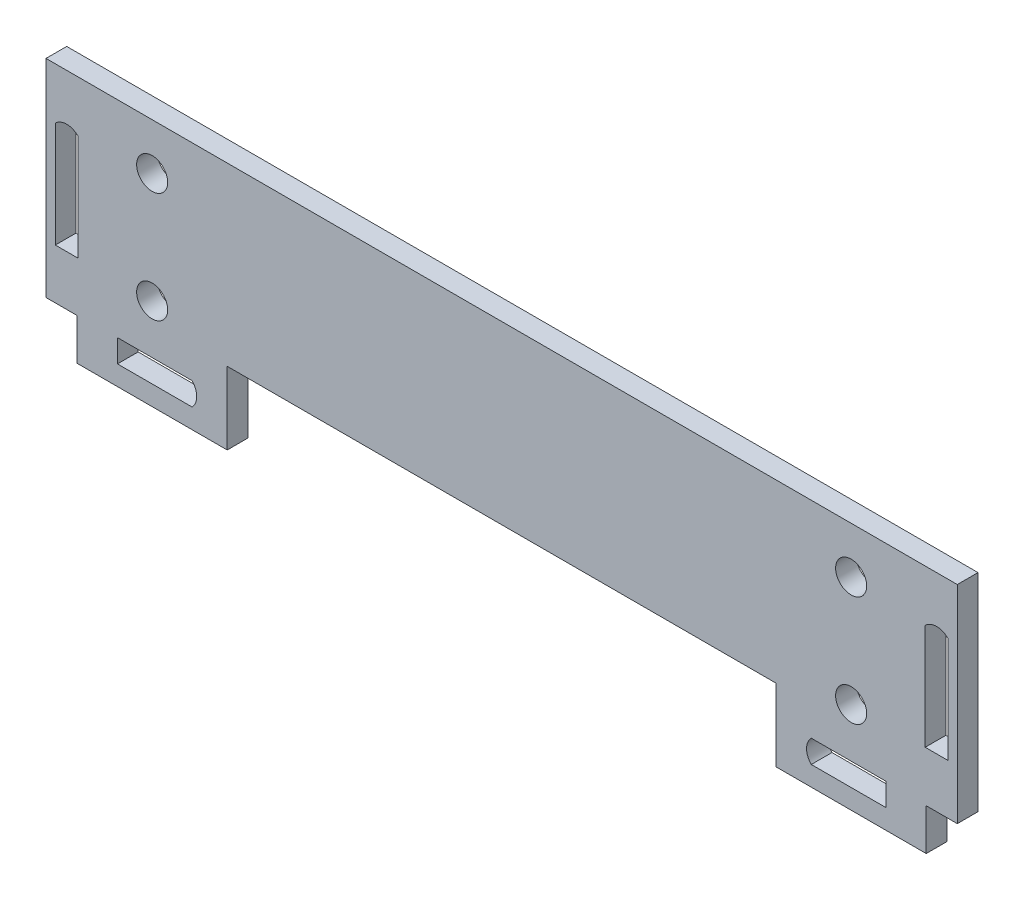
SolidWorks part; units mm, degrees
ref_plane "前视基准面" through (0, 0, 0) normal (0, 0, 1) x (1, 0, 0)
ref_plane "上视基准面" through (0, 0, 0) normal (0, 1, 0) x (1, 0, 0)
ref_plane "右视基准面" through (0, 0, 0) normal (1, 0, 0) x (0, 0, -1)
sketch "草图3" plane through (0, 0, 0) normal (0, 0, 1) x (1, 0, 0)
  line L2 (41, 20.0098) -> (-41, 20.0098)
  line L4 (43.1, 4.8498) -> (40.9, 15.0498) construction
  line L5 (-37, 0.0098) -> (-37, -1.9902) construction
  line L6 (-30, -1.9902) -> (-37, -1.9902) construction
  line L7 (-30, 0.0098) -> (-30, -1.9902) construction
  line L8 (-30, 0.0098) -> (-37, 0.0098) construction
  line L9 (-41, -1.9902) -> (-41, 0.0098) construction
  line L10 (0, -1.9902) -> (0, 3.216) construction
  line L11 (30, 0.0098) -> (37, 0.0098) construction
  line L12 (30, 0.0098) -> (30, -1.9902) construction
  line L13 (30, -1.9902) -> (37, -1.9902) construction
  line L14 (37, 0.0098) -> (37, -1.9902) construction
  line L24 (37.1, -2.0902) -> (29.9, -2.0902)
  line L25 (37.1, -2.0902) -> (37.1, 0.1098)
  line L26 (37.1, 0.1098) -> (29.9, 0.1098)
  line L30 (41, 0.0098) -> (41, -3.9902)
  line L81 (-44, 0.0098) -> (-44, 5.0098)
  line L82 (-41, 0.0098) -> (-44, 0.0098)
  line L87 (-44, 15.0098) -> (-44, 20.0098)
  line L88 (-44, 20.0098) -> (-41, 20.0098)
  line L89 (-41, 0.0098) -> (-41, -3.9902)
  line L90 (-37.1, 0.1098) -> (-29.9, 0.1098)
  line L91 (-37.1, -2.0902) -> (-37.1, 0.1098)
  line L92 (-37.1, -2.0902) -> (-29.9, -2.0902)
  line L93 (41, -3.9902) -> (26.5, -3.9902)
  line L94 (26.5, -3.9902) -> (26.5, 3.0098)
  line L95 (-41, -3.9902) -> (-26.5, -3.9902)
  line L96 (-26.5, -3.9902) -> (-26.5, 3.0098)
  line L98 (-26.5, 3.0098) -> (26.5, 3.0098)
  line L101 (-42, 14.9498) -> (-42, 4.9498) construction
  line L103 (-43.1, 15.0498) -> (-43.1, 4.8498)
  line L104 (-43.1, 4.8498) -> (-40.9, 4.8498)
  line L105 (-40.9, 15.0498) -> (-40.9, 4.8498)
  line L106 (-43.1, 15.0498) -> (-40.9, 4.8498) construction
  line L107 (-43.1, 4.8498) -> (-40.9, 15.0498) construction
  line L108 (-44, 15.0098) -> (-44, 5.0098)
  line L109 (43.1, 15.0498) -> (40.9, 4.8498) construction
  line L110 (42, 14.9498) -> (42, 4.9498) construction
  line L111 (44, 15.0098) -> (44, 5.0098)
  line L112 (40.9, 15.0498) -> (40.9, 4.8498)
  line L113 (43.1, 4.8498) -> (40.9, 4.8498)
  line L114 (43.1, 15.0498) -> (43.1, 4.8498)
  line L116 (44, 20.0098) -> (41, 20.0098)
  line L117 (44, 15.0098) -> (44, 20.0098)
  line L118 (41, 0.0098) -> (44, 0.0098)
  line L119 (44, 0.0098) -> (44, 5.0098)
  arc A2 (29.9, 0.1098) -> (29.9, -2.0902) centre (31, -0.9902) ccw
  arc A3 (-29.9, 0.1098) -> (-29.9, -2.0902) centre (-31, -0.9902) cw
  circle A6 centre (-33.75, 15.5098) radius 1.5
  arc A7 (-43.1, 15.0498) -> (-40.9, 15.0498) centre (-42, 13.9498) cw
  arc A8 (40.9, 15.0498) -> (43.1, 15.0498) centre (42, 13.9498) cw
  circle A9 centre (-33.75, 4.8498) radius 1.5
  circle A11 centre (33.75, 4.8498) radius 1.5
  circle A12 centre (33.75, 15.5098) radius 1.5
  point P4 (0, -3.9902)
  point P14 (-42, 9.9498)
  point P37 (0, 20.0098)
  point P57 (42, 9.9498)
extrude "凸台-拉伸1" add sketch "草图3" along normal blind 2
